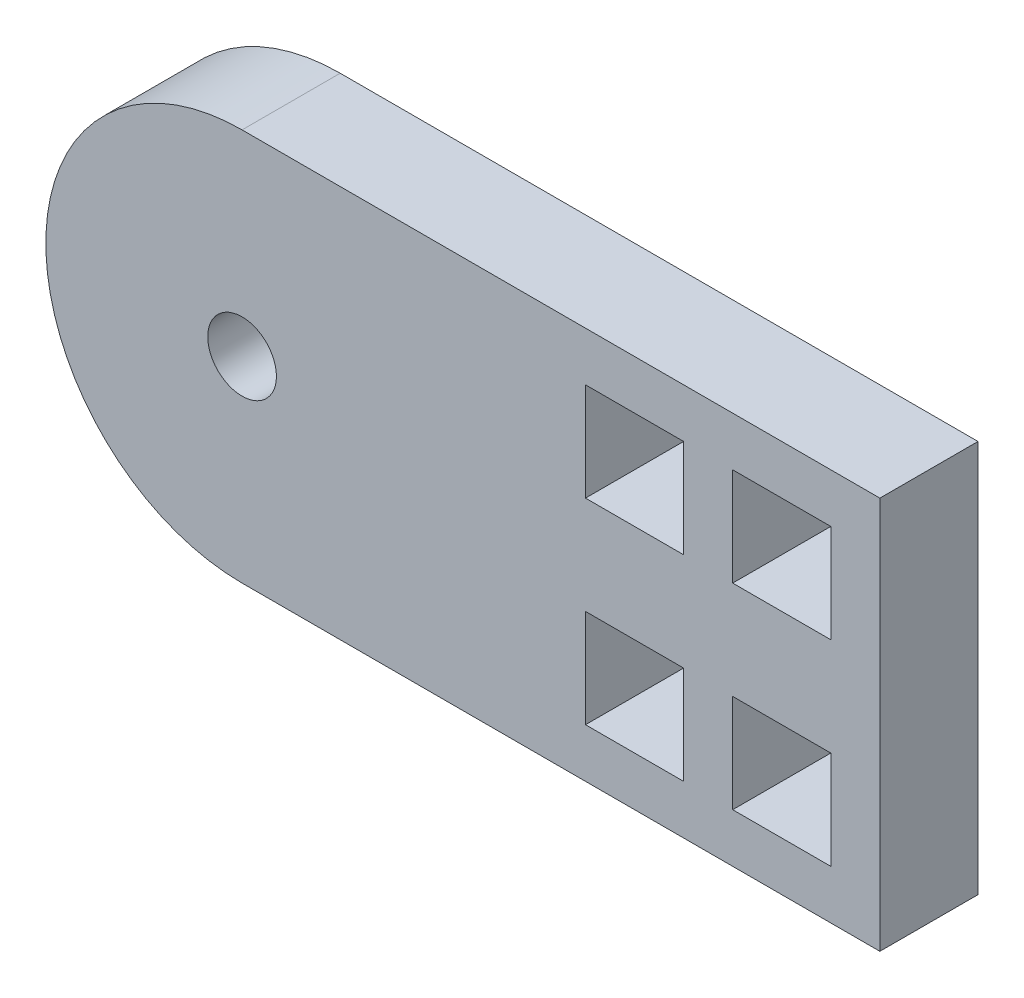
SolidWorks part; units mm, degrees
ref_plane "Front Plane" through (0, 0, 0) normal (0, 0, 1) x (1, 0, 0)
ref_plane "Top Plane" through (0, 0, 0) normal (0, 1, 0) x (1, 0, 0)
ref_plane "Right Plane" through (0, 0, 0) normal (1, 0, 0) x (0, 0, -1)
sketch "Sketch1" plane through (0, 0, 0) normal (0, 0, 1) x (1, 0, 0)
  line L0 (0, 10) -> (32.5, 10)
  line L1 (0, -10) -> (32.5, -10)
  line L2 (32.5, 10) -> (32.5, -10)
  line L4 (25, 7.5) -> (30, 7.5)
  line L5 (25, 7.5) -> (25, 2.5)
  line L6 (25, 2.5) -> (30, 2.5)
  line L7 (30, 7.5) -> (30, 2.5)
  line L8 (25, 7.5) -> (30, 2.5) construction
  line L9 (25, 2.5) -> (30, 7.5) construction
  line L10 (25, -2.5) -> (30, -2.5)
  line L11 (25, -2.5) -> (25, -7.5)
  line L12 (25, -7.5) -> (30, -7.5)
  line L13 (30, -2.5) -> (30, -7.5)
  line L14 (25, -2.5) -> (30, -7.5) construction
  line L15 (25, -7.5) -> (30, -2.5) construction
  line L16 (17.5, -2.5) -> (22.5, -2.5)
  line L17 (17.5, -2.5) -> (17.5, -7.5)
  line L18 (17.5, -7.5) -> (22.5, -7.5)
  line L19 (22.5, -2.5) -> (22.5, -7.5)
  line L20 (17.5, -2.5) -> (22.5, -7.5) construction
  line L21 (17.5, -7.5) -> (22.5, -2.5) construction
  line L22 (17.5, 7.5) -> (22.5, 7.5)
  line L23 (17.5, 7.5) -> (17.5, 2.5)
  line L24 (17.5, 2.5) -> (22.5, 2.5)
  line L25 (22.5, 7.5) -> (22.5, 2.5)
  line L26 (17.5, 7.5) -> (22.5, 2.5) construction
  line L27 (17.5, 2.5) -> (22.5, 7.5) construction
  circle A0 centre (0, 0) radius 1.75
  arc A1 (0, 10) -> (0, -10) centre (0, 0) ccw
  point P8 (27.5, 5)
  point P13 (27.5, -5)
  point P18 (20, -5)
  point P23 (20, 5)
  point P28 (28.701, 6.0138)
  point P29 (36.1684, 6.0138)
  point P30 (36.6814, 5)
  point P31 (36.201, -6.5674)
  dimension "D1" = 3.5
  dimension "D2" = 20
  dimension "D3" = 5
  dimension "D4" = 5
  dimension "D5" = 5
  dimension "D6" = 5
  dimension "D7" = 2.5
  dimension "D8" = 2.5
  dimension "D9" = 2.5
  dimension "D10" = 2.5
  dimension "D11" = 32.5
extrude "Boss-Extrude1" add sketch "Sketch1" along normal blind 5
